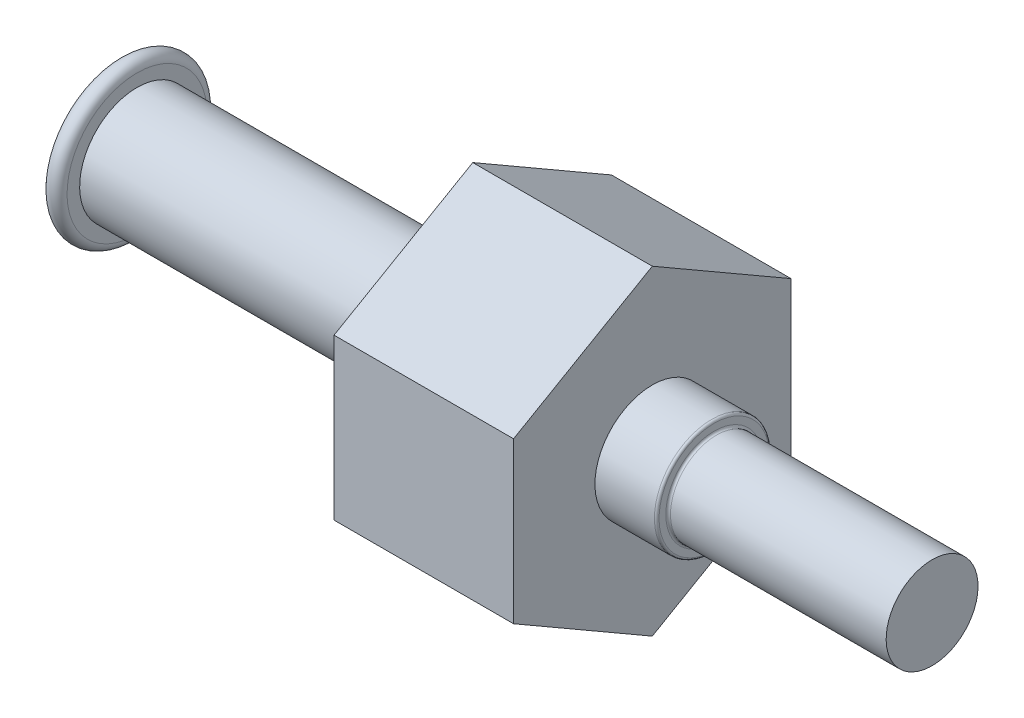
SolidWorks part; units mm, degrees
ref_plane "Front Plane" through (0, 0, 0) normal (0, 0, 1) x (1, 0, 0)
ref_plane "Top Plane" through (0, 0, 0) normal (0, 1, 0) x (1, 0, 0)
ref_plane "Right Plane" through (0, 0, 0) normal (1, 0, 0) x (0, 0, -1)
sketch "Sketch1" plane through (0, 0, 0) normal (0, 0, 1) x (1, 0, 0)
  line L0 (0, 2.46) -> (0, 3)
  line L1 (0, 2.46) -> (24.65, 2.46)
  line L2 (24.75, 2.36) -> (24.75, 2.07)
  line L3 (24.85, 1.97) -> (34.1, 1.97)
  line L4 (34.1, 1.97) -> (34.1, 0)
  line L5 (34.1, 0) -> (-1.25, 0)
  arc A1 (0, 3) -> (-0.7297, 3.1216) centre (-0.375, 3) ccw
  arc A2 (-0.7297, 3.1216) -> (-1.25, 0) centre (8.375, 0) ccw
  arc A3 (24.75, 2.07) -> (24.85, 1.97) centre (24.85, 2.07) ccw
  arc A4 (24.65, 2.46) -> (24.75, 2.36) centre (24.65, 2.36) cw
  point P9 (0, 0)
  point P12 (26.2653, 1.8695)
  point P14 (-0.375, 3.375)
  point P18 (24.75, 2.46)
  dimension "D1" = 0.375
  dimension "D4" = 1.25
  dimension "D8" = 0.1
  dimension "D2" = 35.35
  dimension "D3" = 3.375
  dimension "D5" = 2.46
  dimension "D6" = 26
  dimension "D7" = 1.97
revolve "Revolve1" add sketch "Sketch1" angle 360 about L5
ref_plane "Plane1" through (22.1, 0, 0) normal (1, 0, 0) x (0, 0, -1)
sketch "Sketch2" plane through (22.1, 0, 0) normal (1, 0, 0) x (0, 0, -1)
  line L1 (-5.95, 3.4352) -> (-5.95, -3.4352)
  line L2 (-5.95, -3.4352) -> (0, -6.8705)
  line L3 (0, -6.8705) -> (5.95, -3.4352)
  line L4 (5.95, -3.4352) -> (5.95, 3.4352)
  line L5 (5.95, 3.4352) -> (0, 6.8705)
  line L6 (0, 6.8705) -> (-5.95, 3.4352)
  circle A0 centre (0, 0) radius 5.95 construction
  point P1 (0, -6.8705)
  dimension "D1" = 11.9
extrude "Boss-Extrude1" add sketch "Sketch2" against normal blind 7.7
